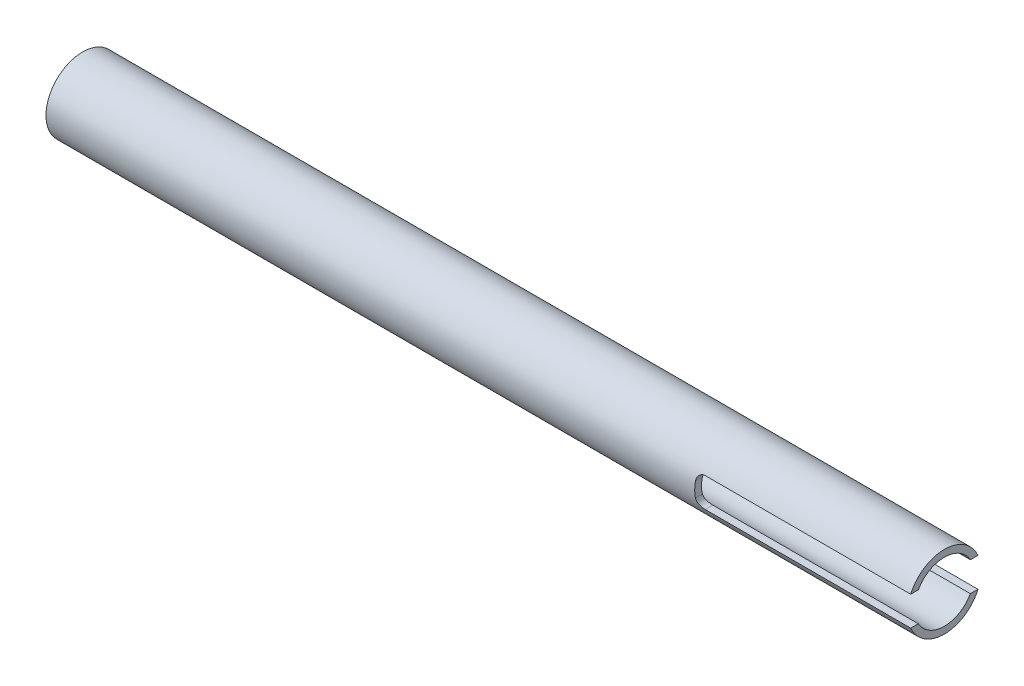
SolidWorks part; units mm, degrees
material "AISI 4130 Steel, annealed at 865C"
ref_plane "X-Y Datum" through (0, 0, 0) normal (0, 0, 1) x (1, 0, 0)
ref_plane "X-Z Datum" through (0, 0, 0) normal (0, 1, 0) x (1, 0, 0)
ref_plane "Y-Z Datum" through (0, 0, 0) normal (1, 0, 0) x (0, 0, -1)
sketch "Sketch1" plane through (0, 0, 0) normal (1, 0, 0) x (0, 0, -1)
  circle A0 centre (0, 0) radius 6.4643
  circle A1 centre (0, 0) radius 7.9375
  dimension "D1" = 15.875
  dimension "D2" = 12.9286
extrude "Boss-Extrude1" add sketch "Sketch1" along normal offset from surface 44.45 and the other way up to surface (87.6746 mm away)
ref_plane "Plane1" through (0, 0, -7.9375) normal (0, 0, -1) x (-1, 0, 0)
sketch "Sketch2" plane through (0, 0, -7.9375) normal (0, 0, -1) x (-1, 0, 0)
  line L0 (-55.7478, -3.175) -> (-54.1603, -3.175) construction
  line L1 (-106.8653, -3.175) -> (-55.7478, -3.175) construction
  line L3 (-54.1603, 3.175) -> (-55.7478, 3.175) construction
  line L4 (-55.7478, 3.175) -> (-106.8653, 3.175) construction
  line L5 (-55.7478, -3.175) -> (-54.1603, -3.175)
  line L6 (-106.8653, -3.175) -> (-55.7478, -3.175)
  line L8 (-54.1603, 3.175) -> (-55.7478, 3.175)
  line L9 (-55.7478, 3.175) -> (-106.8653, 3.175)
  line L10 (-106.8653, 3.175) -> (-106.8653, -3.175)
  line L11 (-54.1603, 3.175) -> (-52.5728, 3.175)
  line L12 (-52.5728, 3.175) -> (-52.5728, -3.175)
  line L13 (-52.5728, -3.175) -> (-54.1603, -3.175)
  dimension "D1" = 1.5875
extrude "Cut-Extrude1" cut sketch "Sketch2" against normal through all
fillet "Fillet1" radius 1.5875 3 edges at (52.5728, 3.175, 6.4528) (52.5728, 3.175, -6.4528) (52.5728, -3.175, -6.4528)
